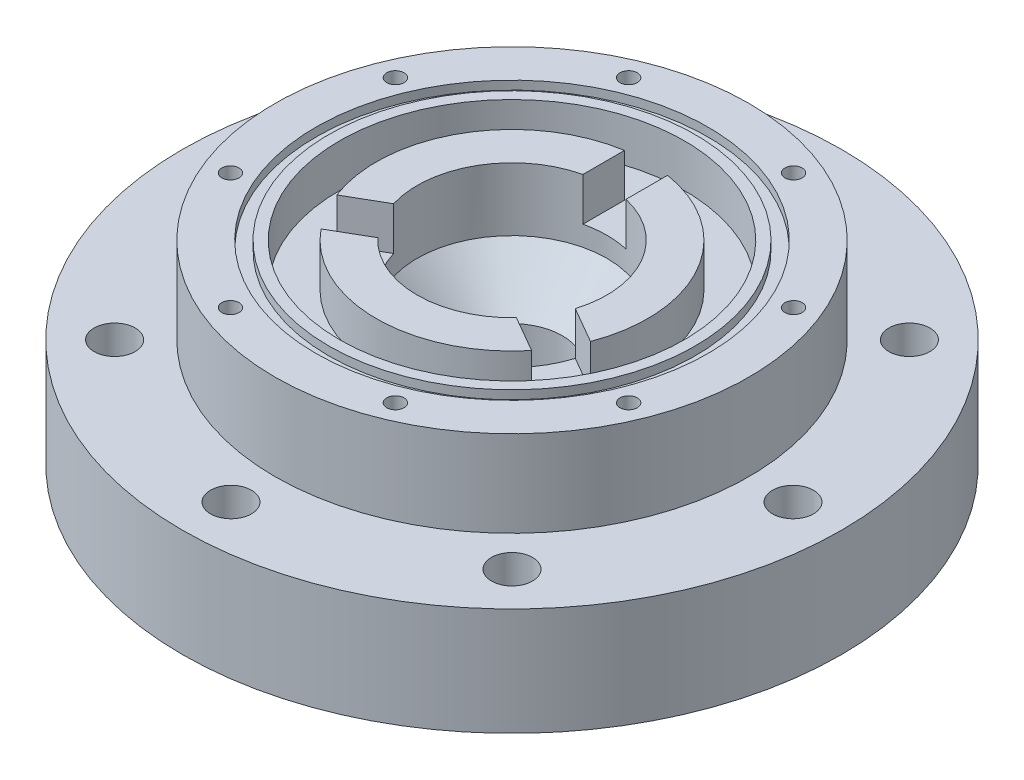
SolidWorks part; units mm, degrees
material "AISI 1020"
ref_plane "Front Plane" through (0, 0, 0) normal (0, 0, 1) x (1, 0, 0)
ref_plane "Top Plane" through (0, 0, 0) normal (0, 1, 0) x (1, 0, 0)
ref_plane "Right Plane" through (0, 0, 0) normal (1, 0, 0) x (0, 0, -1)
sketch "Sketch3" plane through (0, 0, 0) normal (1, 0, 0) x (0, 0, -1)
  line L2 (76.5, 15) -> (55, 15)
  line L3 (55, 15) -> (55, 35)
  line L4 (55, 35) -> (22.025, 35)
  line L7 (11.665, 0) -> (16.665, 0)
  line L8 (76.5, 15) -> (76.5, -10)
  line L9 (53.85, -10) -> (53.85, 86.2223) construction
  line L10 (76.5, -10) -> (53.85, -10)
  line L11 (11.665, 0) -> (11.665, 10)
  line L12 (11.665, 10) -> (22.025, 20.36)
  line L13 (22.025, 20.36) -> (22.025, 35)
  line L14 (0, 0) -> (0, 51.2471) construction
  line L15 (11.665, 10) -> (19.7366, 10) construction
  line L16 (65.2, -29.1535) -> (65.2, 61.9555) construction
  line L17 (0, 0) -> (11.665, 0) construction
  arc A3 (53.85, -10) -> (16.665, 0) centre (30.7197, -21.8739) ccw
  dimension "D6" = 26
  dimension "D1" = 10
  dimension "D2" = 55
  dimension "D3" = 76.5
  dimension "D4" = 45
  dimension "D5" = 53.85
  dimension "D7" = 11.665
  dimension "D9" = 25
  dimension "D11" = 10
  dimension "D12" = 45
  dimension "D13" = 44.05
  dimension "D14" = 5
  dimension "D15" = 65.2
revolve "Revolve1" add sketch "Sketch3" angle 360 about L14
sketch "Sketch4" plane through (0, 0, 0) normal (0, 1, 0) x (1, 0, 0)
  line L0 (0, 0) -> (-65.2, 0) construction
  circle A0 centre (-65.2, 0) radius 4.7625
  dimension "D2" = 9.525
  dimension "D1" = 65.2
extrude "Cut-Extrude2" cut sketch "Sketch4" along normal through all both and the other way through all contours A0
pattern_circular "CirPattern1" count 8 over 360 about axis through (0, 0, 0) along (0, 1, 0) of "Cut-Extrude2"
sketch "Sketch6" plane through (0, 35, 0) normal (0, 1, 0) x (1, 0, 0)
  circle A0 centre (0, 0) radius 31.5
  circle A1 centre (0, 0) radius 40
  point P19 (0, 0)
  dimension "D1" = 63
  dimension "D2" = 80
extrude "Cut-Extrude3" cut sketch "Sketch6" against normal blind 10
sketch "Sketch7" plane through (0, 35, 0) normal (0, 1, 0) x (1, 0, 0)
  line L0 (0, 0) -> (0, 31.5) construction
  line L1 (-5, 31.5) -> (5, 31.5)
  line L2 (5, 31.5) -> (5, 21.45)
  line L3 (5, 21.45) -> (-5, 21.45)
  line L4 (-5, 21.45) -> (-5, 31.5)
  circle A0 centre (0, 0) radius 31.5 construction
  circle A1 centre (0, 0) radius 22.025 construction
  point P8 (0, 31.5)
  dimension "D1" = 10
extrude "Cut-Extrude4" cut sketch "Sketch7" against normal blind 10
pattern_circular "CirPattern2" count 3 over 360 about axis through (0, 0, 0) along (0, 1, 0) of "Cut-Extrude4"
sketch "Sketch9" plane through (0, 35, 0) normal (0, 1, 0) x (1, 0, 0)
  line L0 (0, 0) -> (46.194, 19.1342) construction
  line L1 (0, 0) -> (100.5921, 0) construction
  circle A0 centre (46.194, 19.1342) radius 2
  dimension "D2" = 4
  dimension "D1" = 50
  dimension "D3" = 22.5
extrude "Cut-Extrude5" cut sketch "Sketch9" against normal blind 10
pattern_circular "CirPattern3" count 8 over 360 about axis through (0, 0, 0) along (0, 1, 0) of "Cut-Extrude5"
sketch "Sketch10" plane through (0, 35, 0) normal (0, 1, 0) x (1, 0, 0)
  circle A0 centre (0, 0) radius 42.5
  circle A1 centre (0, 0) radius 45.5
  dimension "D1" = 3
  dimension "D2" = 85
extrude "Cut-Extrude6" cut sketch "Sketch10" against normal blind 2
